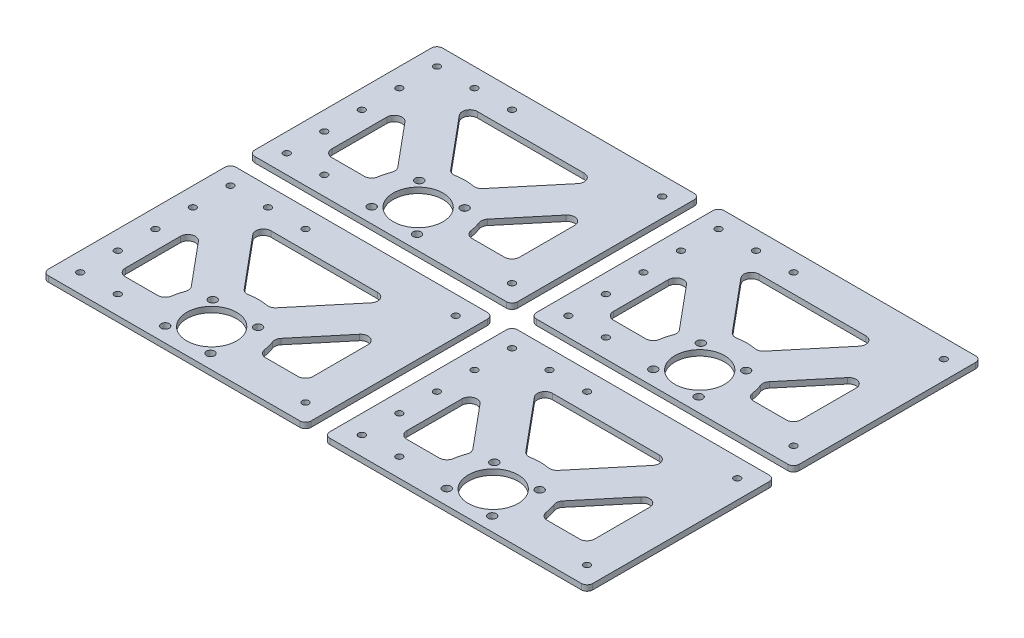
SolidWorks part; units mm, degrees
ref_plane "前视基准面" through (0, 0, 0) normal (0, 0, 1) x (1, 0, 0)
ref_plane "上视基准面" through (0, 0, 0) normal (0, 1, 0) x (1, 0, 0)
ref_plane "右视基准面" through (0, 0, 0) normal (1, 0, 0) x (0, 0, -1)
sketch "草图1" plane through (0, 0, 0) normal (0, 1, 0) x (1, 0, 0)
  line L1 (-70, -50) -> (70, -50)
  line L2 (-70, -50) -> (-70, 50)
  line L3 (-70, 50) -> (70, 50)
  line L4 (70, -50) -> (70, 50)
  line L5 (-70, -50) -> (70, 50) construction
  line L6 (-70, 50) -> (70, -50) construction
  point P0 (0, 0)
  point P10 (46.8172, -33.4409)
  point P11 (48.0271, -34.3051)
  point P12 (0, 0)
  dimension "D1" = 140
  dimension "D2" = 100
extrude "凸台-拉伸1" add sketch "草图1" along normal blind 3
sketch "草图2" plane through (0, 3, 0) normal (0, 1, 0) x (1, 0, 0)
  line L0 (-50, 30) -> (0, -30) construction
  line L1 (-50, -30) -> (50, -30)
  line L2 (-50, -30) -> (-50, 30)
  line L3 (-50, 30) -> (50, 30)
  line L4 (50, -30) -> (50, 30)
  line L5 (-50, -30) -> (50, 30) construction
  line L6 (-50, 30) -> (50, -30) construction
  line L7 (-42.3178, 36.4018) -> (7.6822, -23.5982) construction
  line L8 (-57.6822, 23.5982) -> (-7.6822, -36.4018) construction
  line L9 (-50, 30) -> (-50, 14.3795)
  line L10 (-50, 14.3795) -> (-22.3507, -18.7997)
  line L11 (-22.3507, -18.7997) -> (-6.9863, -5.996)
  line L12 (-6.9863, -5.996) -> (-36.9829, 30)
  line L13 (-36.9829, 30) -> (-50, 30)
  line L14 (0, 0) -> (0, 13.0008) construction
  line L15 (6.9863, -5.996) -> (36.9829, 30)
  line L16 (22.3507, -18.7997) -> (6.9863, -5.996)
  line L17 (50, 14.3795) -> (22.3507, -18.7997)
  line L18 (50, 30) -> (50, 14.3795)
  line L19 (36.9829, 30) -> (50, 30)
  circle A0 centre (0, -30) radius 13.25
  circle A1 centre (0, -30) radius 25
  circle A2 centre (0, -30) radius 17.5 construction
  circle A3 centre (-12.0799, -17.338) radius 2.15
  circle A4 centre (12.662, -17.9201) radius 2.15
  circle A5 centre (12.0799, -42.662) radius 2.15
  circle A6 centre (-12.662, -42.0799) radius 2.15
  arc A7 (-42.3178, 36.4018) -> (-57.6822, 23.5982) centre (-50, 30) ccw construction
  arc A8 (-7.6822, -36.4018) -> (7.6822, -23.5982) centre (0, -30) ccw construction
  point P0 (0, 0)
  point P11 (-25, 0)
  dimension "D3" = 26.5
  dimension "D4" = 50
  dimension "D5" = 35
  dimension "D6" = 4
  dimension "D7" = 4.3
  dimension "D8" = 10
  dimension "D1" = 100
  dimension "D2" = 60
extrude "切除-拉伸1" cut sketch "草图2" against normal up to next contours A1 L10 L2 L1 | A1 L15 L3 L12 | A1 L1 L4 L17 | A4 | A3 | A6 | A5 | L1 A0 | L1 A0
fillet "圆角1" radius 4 12 edges at (-50, 1.5, 30) (25, 1.5, 30) (-25, 1.5, 30) (-22.3507, 1.5, 18.7997) (22.3507, 1.5, 18.7997) (50, 1.5, 30) (50, 1.5, -14.3795) (-6.9863, 1.5, 5.996) (6.9863, 1.5, 5.996) (36.9829, 1.5, -30) (-36.9829, 1.5, -30) (-50, 1.5, -14.3795)
fillet "圆角2" radius 3 4 edges at (70, 1.5, -50) (70, 1.5, 50) (-70, 1.5, 50) (-70, 1.5, -50)
sketch "草图3" plane through (0, 3, 0) normal (0, 1, 0) x (1, 0, 0)
  line L0 (-67, -50) -> (67, -50) construction
  line L1 (-70, 47) -> (-70, -47) construction
  line L2 (-60, -40) -> (-40, -40) construction
  line L3 (-60, -40) -> (-60, -20) construction
  line L4 (-60, 40) -> (-40, 40) construction
  line L5 (-60, -40) -> (60, -40) construction
  circle A0 centre (-60, -40) radius 1.75
  circle A1 centre (-40, -40) radius 1.75
  circle A2 centre (-60, -20) radius 1.75
  circle A3 centre (-60, 0) radius 1.75
  circle A4 centre (-60, 20) radius 1.75
  circle A5 centre (-60, 40) radius 1.75
  circle A6 centre (-40, 40) radius 1.75
  circle A7 centre (-20, 40) radius 1.75
  circle A8 centre (60, -40) radius 1.75
  circle A9 centre (60, 40) radius 1.75
  dimension "D1" = 10
  dimension "D3" = 3.5
  dimension "D2" = 10
  dimension "D5" = 20
  dimension "D7" = 20
  dimension "D9" = 20
  dimension "D11" = 120
  dimension "D4" = 2
  dimension "D6" = 5
  dimension "D8" = 3
  dimension "D10" = 2
extrude "切除-拉伸2" cut sketch "草图3" against normal up to next
sketch "草图4" plane through (0, 3, 0) normal (0, 1, 0) x (1, 0, 0)
  line L4 (70, -47) -> (70, 47)
  line L5 (67, 50) -> (-67, 50)
  line L6 (-70, 47) -> (-70, -47)
  line L7 (-67, -50) -> (67, -50)
  line L8 (70, -47) -> (70, 47)
  line L9 (67, 50) -> (-67, 50)
  line L10 (-70, 47) -> (-70, -47)
  line L11 (-67, -50) -> (67, -50)
  line L29 (-46, -30) -> (-28.7228, -30) construction
  line L30 (-42.9271, 5.892) -> (-23.9409, -16.8914) construction
  line L31 (-50, -26) -> (-50, 3.3313) construction
  line L32 (8.5765, -4.0878) -> (31.5156, 23.4393) construction
  line L33 (-8.5765, -4.0878) -> (-31.5156, 23.4393) construction
  line L34 (-28.4428, 30) -> (28.4428, 30) construction
  line L35 (28.7228, -30) -> (46, -30) construction
  line L36 (50, -26) -> (50, 3.3313) construction
  line L37 (42.9271, 5.892) -> (23.9409, -16.8914) construction
  line L38 (42.9271, 5.892) -> (23.9409, -16.8914)
  line L39 (50, -26) -> (50, 3.3313)
  line L40 (28.7228, -30) -> (46, -30)
  line L41 (-28.4428, 30) -> (28.4428, 30)
  line L42 (-8.5765, -4.0878) -> (-31.5156, 23.4393)
  line L43 (8.5765, -4.0878) -> (31.5156, 23.4393)
  line L44 (-50, -26) -> (-50, 3.3313)
  line L45 (-42.9271, 5.892) -> (-23.9409, -16.8914)
  line L46 (-46, -30) -> (-28.7228, -30)
  line L47 (220, -47) -> (220, 47)
  line L48 (217, 50) -> (83, 50)
  line L49 (80, 47) -> (80, -47)
  line L50 (83, -50) -> (217, -50)
  line L51 (192.9271, 5.892) -> (173.9409, -16.8914)
  line L52 (200, -26) -> (200, 3.3313)
  line L53 (178.7228, -30) -> (196, -30)
  line L54 (121.5572, 30) -> (178.4428, 30)
  line L55 (141.4235, -4.0878) -> (118.4844, 23.4393)
  line L56 (158.5765, -4.0878) -> (181.5156, 23.4393)
  line L57 (100, -26) -> (100, 3.3313)
  line L58 (107.0729, 5.892) -> (126.0591, -16.8914)
  line L59 (104, -30) -> (121.2772, -30)
  line L60 (220, 63) -> (220, 157)
  line L61 (217, 160) -> (83, 160)
  line L62 (80, 157) -> (80, 63)
  line L63 (83, 60) -> (217, 60)
  line L64 (192.9271, 115.892) -> (173.9409, 93.1086)
  line L65 (200, 84) -> (200, 113.3313)
  line L66 (178.7228, 80) -> (196, 80)
  line L67 (121.5572, 140) -> (178.4428, 140)
  line L68 (141.4235, 105.9122) -> (118.4844, 133.4393)
  line L69 (158.5765, 105.9122) -> (181.5156, 133.4393)
  line L70 (100, 84) -> (100, 113.3313)
  line L71 (107.0729, 115.892) -> (126.0591, 93.1086)
  line L72 (104, 80) -> (121.2772, 80)
  line L73 (70, 63) -> (70, 157)
  line L74 (67, 160) -> (-67, 160)
  line L75 (-70, 157) -> (-70, 63)
  line L76 (-67, 60) -> (67, 60)
  line L77 (42.9271, 115.892) -> (23.9409, 93.1086)
  line L78 (50, 84) -> (50, 113.3313)
  line L79 (28.7228, 80) -> (46, 80)
  line L80 (-28.4428, 140) -> (28.4428, 140)
  line L81 (-8.5765, 105.9122) -> (-31.5156, 133.4393)
  line L82 (8.5765, 105.9122) -> (31.5156, 133.4393)
  line L83 (-50, 84) -> (-50, 113.3313)
  line L84 (-42.9271, 115.892) -> (-23.9409, 93.1086)
  line L85 (-46, 80) -> (-28.7228, 80)
  line L86 (70, -47) -> (220, -47) construction
  line L87 (70, -47) -> (70, 63) construction
  arc A4 (70, 47) -> (67, 50) centre (67, 47) ccw
  arc A5 (-67, 50) -> (-70, 47) centre (-67, 47) ccw
  arc A6 (-70, -47) -> (-67, -50) centre (-67, -47) ccw
  arc A7 (67, -50) -> (70, -47) centre (67, -47) ccw
  arc A8 (70, 47) -> (67, 50) centre (67, 47) ccw
  arc A9 (-67, 50) -> (-70, 47) centre (-67, 47) ccw
  arc A10 (-70, -47) -> (-67, -50) centre (-67, -47) ccw
  arc A11 (67, -50) -> (70, -47) centre (67, -47) ccw
  circle A50 centre (-20, 40) radius 1.75 construction
  circle A51 centre (-40, 40) radius 1.75 construction
  circle A52 centre (-60, 40) radius 1.75 construction
  circle A53 centre (-60, 20) radius 1.75 construction
  circle A54 centre (-60, 0) radius 1.75 construction
  circle A55 centre (-60, -20) radius 1.75 construction
  circle A56 centre (-60, -40) radius 1.75 construction
  arc A57 (-42.9271, 5.892) -> (-50, 3.3313) centre (-46, 3.3313) ccw construction
  arc A58 (-50, -26) -> (-46, -30) centre (-46, -26) ccw construction
  arc A59 (-28.7228, -30) -> (-24.761, -26.5517) centre (-28.7228, -26) ccw construction
  arc A60 (-23.2877, -20.9071) -> (-24.761, -26.5517) centre (0, -30) ccw construction
  circle A61 centre (-40, -40) radius 1.75 construction
  circle A62 centre (-12.662, -42.0799) radius 2.15 construction
  circle A63 centre (0, -30) radius 13.25 construction
  circle A64 centre (12.0799, -42.662) radius 2.15 construction
  circle A65 centre (12.662, -17.9201) radius 2.15 construction
  circle A66 centre (-12.0799, -17.338) radius 2.15 construction
  arc A67 (-23.2877, -20.9071) -> (-23.9409, -16.8914) centre (-27.0138, -19.4522) ccw construction
  arc A68 (4.7445, -5.4543) -> (-4.7445, -5.4543) centre (0, -30) ccw construction
  arc A69 (-8.5765, -4.0878) -> (-4.7445, -5.4543) centre (-5.5036, -1.527) ccw construction
  arc A70 (4.7445, -5.4543) -> (8.5765, -4.0878) centre (5.5036, -1.527) ccw construction
  arc A71 (-28.4428, 30) -> (-31.5156, 23.4393) centre (-28.4428, 26) ccw construction
  arc A72 (31.5156, 23.4393) -> (28.4428, 30) centre (28.4428, 26) ccw construction
  arc A73 (50, 3.3313) -> (42.9271, 5.892) centre (46, 3.3313) ccw construction
  arc A74 (24.761, -26.5517) -> (23.2877, -20.9071) centre (0, -30) ccw construction
  arc A75 (23.9409, -16.8914) -> (23.2877, -20.9071) centre (27.0138, -19.4522) ccw construction
  arc A76 (24.761, -26.5517) -> (28.7228, -30) centre (28.7228, -26) ccw construction
  arc A77 (46, -30) -> (50, -26) centre (46, -26) ccw construction
  circle A78 centre (60, 40) radius 1.75 construction
  circle A79 centre (60, -40) radius 1.75 construction
  circle A80 centre (60, -40) radius 1.75
  circle A81 centre (60, 40) radius 1.75
  arc A82 (46, -30) -> (50, -26) centre (46, -26) ccw
  arc A83 (24.761, -26.5517) -> (28.7228, -30) centre (28.7228, -26) ccw
  arc A84 (23.9409, -16.8914) -> (23.2877, -20.9071) centre (27.0138, -19.4522) ccw
  arc A85 (24.761, -26.5517) -> (23.2877, -20.9071) centre (0, -30) ccw
  arc A86 (50, 3.3313) -> (42.9271, 5.892) centre (46, 3.3313) ccw
  arc A87 (31.5156, 23.4393) -> (28.4428, 30) centre (28.4428, 26) ccw
  arc A88 (-28.4428, 30) -> (-31.5156, 23.4393) centre (-28.4428, 26) ccw
  arc A89 (4.7445, -5.4543) -> (8.5765, -4.0878) centre (5.5036, -1.527) ccw
  arc A90 (-8.5765, -4.0878) -> (-4.7445, -5.4543) centre (-5.5036, -1.527) ccw
  arc A91 (4.7445, -5.4543) -> (-4.7445, -5.4543) centre (0, -30) ccw
  arc A92 (-23.2877, -20.9071) -> (-23.9409, -16.8914) centre (-27.0138, -19.4522) ccw
  circle A93 centre (-12.0799, -17.338) radius 2.15
  circle A94 centre (12.662, -17.9201) radius 2.15
  circle A95 centre (12.0799, -42.662) radius 2.15
  circle A96 centre (0, -30) radius 13.25
  circle A97 centre (-12.662, -42.0799) radius 2.15
  circle A98 centre (-40, -40) radius 1.75
  arc A99 (-23.2877, -20.9071) -> (-24.761, -26.5517) centre (0, -30) ccw
  arc A100 (-28.7228, -30) -> (-24.761, -26.5517) centre (-28.7228, -26) ccw
  arc A101 (-50, -26) -> (-46, -30) centre (-46, -26) ccw
  arc A102 (-42.9271, 5.892) -> (-50, 3.3313) centre (-46, 3.3313) ccw
  circle A103 centre (-60, -40) radius 1.75
  circle A104 centre (-60, -20) radius 1.75
  circle A105 centre (-60, 0) radius 1.75
  circle A106 centre (-60, 20) radius 1.75
  circle A107 centre (-60, 40) radius 1.75
  circle A108 centre (-40, 40) radius 1.75
  circle A109 centre (-20, 40) radius 1.75
  arc A110 (220, 47) -> (217, 50) centre (217, 47) ccw
  arc A111 (83, 50) -> (80, 47) centre (83, 47) ccw
  arc A112 (80, -47) -> (83, -50) centre (83, -47) ccw
  arc A113 (217, -50) -> (220, -47) centre (217, -47) ccw
  circle A114 centre (210, -40) radius 1.75
  circle A115 centre (210, 40) radius 1.75
  arc A116 (196, -30) -> (200, -26) centre (196, -26) ccw
  arc A117 (174.761, -26.5517) -> (178.7228, -30) centre (178.7228, -26) ccw
  arc A118 (173.9409, -16.8914) -> (173.2877, -20.9071) centre (177.0138, -19.4522) ccw
  arc A119 (174.761, -26.5517) -> (173.2877, -20.9071) centre (150, -30) ccw
  arc A120 (200, 3.3313) -> (192.9271, 5.892) centre (196, 3.3313) ccw
  arc A121 (181.5156, 23.4393) -> (178.4428, 30) centre (178.4428, 26) ccw
  arc A122 (121.5572, 30) -> (118.4844, 23.4393) centre (121.5572, 26) ccw
  arc A123 (154.7445, -5.4543) -> (158.5765, -4.0878) centre (155.5036, -1.527) ccw
  arc A124 (141.4235, -4.0878) -> (145.2555, -5.4543) centre (144.4964, -1.527) ccw
  arc A125 (154.7445, -5.4543) -> (145.2555, -5.4543) centre (150, -30) ccw
  arc A126 (126.7123, -20.9071) -> (126.0591, -16.8914) centre (122.9862, -19.4522) ccw
  circle A127 centre (137.9201, -17.338) radius 2.15
  circle A128 centre (162.662, -17.9201) radius 2.15
  circle A129 centre (162.0799, -42.662) radius 2.15
  circle A130 centre (150, -30) radius 13.25
  circle A131 centre (137.338, -42.0799) radius 2.15
  circle A132 centre (110, -40) radius 1.75
  arc A133 (126.7123, -20.9071) -> (125.239, -26.5517) centre (150, -30) ccw
  arc A134 (121.2772, -30) -> (125.239, -26.5517) centre (121.2772, -26) ccw
  arc A135 (100, -26) -> (104, -30) centre (104, -26) ccw
  arc A136 (107.0729, 5.892) -> (100, 3.3313) centre (104, 3.3313) ccw
  circle A137 centre (90, -40) radius 1.75
  circle A138 centre (90, -20) radius 1.75
  circle A139 centre (90, 0) radius 1.75
  circle A140 centre (90, 20) radius 1.75
  circle A141 centre (90, 40) radius 1.75
  circle A142 centre (110, 40) radius 1.75
  circle A143 centre (130, 40) radius 1.75
  arc A144 (220, 157) -> (217, 160) centre (217, 157) ccw
  arc A145 (83, 160) -> (80, 157) centre (83, 157) ccw
  arc A146 (80, 63) -> (83, 60) centre (83, 63) ccw
  arc A147 (217, 60) -> (220, 63) centre (217, 63) ccw
  circle A148 centre (210, 70) radius 1.75
  circle A149 centre (210, 150) radius 1.75
  arc A150 (196, 80) -> (200, 84) centre (196, 84) ccw
  arc A151 (174.761, 83.4483) -> (178.7228, 80) centre (178.7228, 84) ccw
  arc A152 (173.9409, 93.1086) -> (173.2877, 89.0929) centre (177.0138, 90.5478) ccw
  arc A153 (174.761, 83.4483) -> (173.2877, 89.0929) centre (150, 80) ccw
  arc A154 (200, 113.3313) -> (192.9271, 115.892) centre (196, 113.3313) ccw
  arc A155 (181.5156, 133.4393) -> (178.4428, 140) centre (178.4428, 136) ccw
  arc A156 (121.5572, 140) -> (118.4844, 133.4393) centre (121.5572, 136) ccw
  arc A157 (154.7445, 104.5457) -> (158.5765, 105.9122) centre (155.5036, 108.473) ccw
  arc A158 (141.4235, 105.9122) -> (145.2555, 104.5457) centre (144.4964, 108.473) ccw
  arc A159 (154.7445, 104.5457) -> (145.2555, 104.5457) centre (150, 80) ccw
  arc A160 (126.7123, 89.0929) -> (126.0591, 93.1086) centre (122.9862, 90.5478) ccw
  circle A161 centre (137.9201, 92.662) radius 2.15
  circle A162 centre (162.662, 92.0799) radius 2.15
  circle A163 centre (162.0799, 67.338) radius 2.15
  circle A164 centre (150, 80) radius 13.25
  circle A165 centre (137.338, 67.9201) radius 2.15
  circle A166 centre (110, 70) radius 1.75
  arc A167 (126.7123, 89.0929) -> (125.239, 83.4483) centre (150, 80) ccw
  arc A168 (121.2772, 80) -> (125.239, 83.4483) centre (121.2772, 84) ccw
  arc A169 (100, 84) -> (104, 80) centre (104, 84) ccw
  arc A170 (107.0729, 115.892) -> (100, 113.3313) centre (104, 113.3313) ccw
  circle A171 centre (90, 70) radius 1.75
  circle A172 centre (90, 90) radius 1.75
  circle A173 centre (90, 110) radius 1.75
  circle A174 centre (90, 130) radius 1.75
  circle A175 centre (90, 150) radius 1.75
  circle A176 centre (110, 150) radius 1.75
  circle A177 centre (130, 150) radius 1.75
  arc A178 (70, 157) -> (67, 160) centre (67, 157) ccw
  arc A179 (-67, 160) -> (-70, 157) centre (-67, 157) ccw
  arc A180 (-70, 63) -> (-67, 60) centre (-67, 63) ccw
  arc A181 (67, 60) -> (70, 63) centre (67, 63) ccw
  circle A182 centre (60, 70) radius 1.75
  circle A183 centre (60, 150) radius 1.75
  arc A184 (46, 80) -> (50, 84) centre (46, 84) ccw
  arc A185 (24.761, 83.4483) -> (28.7228, 80) centre (28.7228, 84) ccw
  arc A186 (23.9409, 93.1086) -> (23.2877, 89.0929) centre (27.0138, 90.5478) ccw
  arc A187 (24.761, 83.4483) -> (23.2877, 89.0929) centre (0, 80) ccw
  arc A188 (50, 113.3313) -> (42.9271, 115.892) centre (46, 113.3313) ccw
  arc A189 (31.5156, 133.4393) -> (28.4428, 140) centre (28.4428, 136) ccw
  arc A190 (-28.4428, 140) -> (-31.5156, 133.4393) centre (-28.4428, 136) ccw
  arc A191 (4.7445, 104.5457) -> (8.5765, 105.9122) centre (5.5036, 108.473) ccw
  arc A192 (-8.5765, 105.9122) -> (-4.7445, 104.5457) centre (-5.5036, 108.473) ccw
  arc A193 (4.7445, 104.5457) -> (-4.7445, 104.5457) centre (0, 80) ccw
  arc A194 (-23.2877, 89.0929) -> (-23.9409, 93.1086) centre (-27.0138, 90.5478) ccw
  circle A195 centre (-12.0799, 92.662) radius 2.15
  circle A196 centre (12.662, 92.0799) radius 2.15
  circle A197 centre (12.0799, 67.338) radius 2.15
  circle A198 centre (0, 80) radius 13.25
  circle A199 centre (-12.662, 67.9201) radius 2.15
  circle A200 centre (-40, 70) radius 1.75
  arc A201 (-23.2877, 89.0929) -> (-24.761, 83.4483) centre (0, 80) ccw
  arc A202 (-28.7228, 80) -> (-24.761, 83.4483) centre (-28.7228, 84) ccw
  arc A203 (-50, 84) -> (-46, 80) centre (-46, 84) ccw
  arc A204 (-42.9271, 115.892) -> (-50, 113.3313) centre (-46, 113.3313) ccw
  circle A205 centre (-60, 70) radius 1.75
  circle A206 centre (-60, 90) radius 1.75
  circle A207 centre (-60, 110) radius 1.75
  circle A208 centre (-60, 130) radius 1.75
  circle A209 centre (-60, 150) radius 1.75
  circle A210 centre (-40, 150) radius 1.75
  circle A211 centre (-20, 150) radius 1.75
  dimension "D4" = 150
  dimension "D5" = 110
  dimension "D1" = 0
  dimension "D2" = 2
  dimension "D3" = 2
extrude "凸台-拉伸2" add sketch "草图4" against normal blind 3
